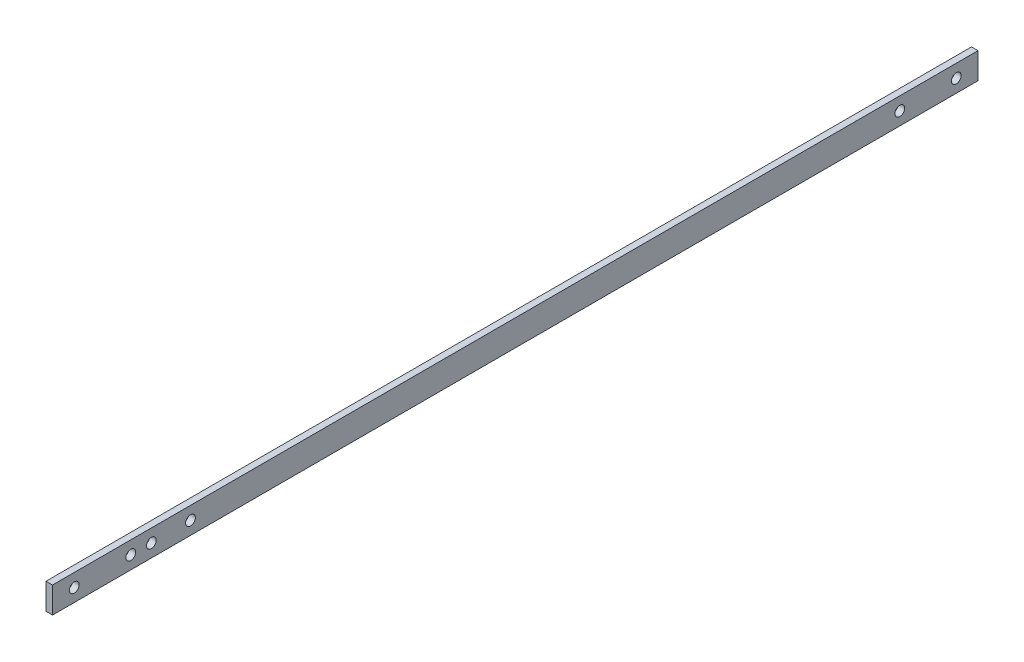
SolidWorks part; units mm, degrees
ref_plane "前视基准面" through (0, 0, 0) normal (0, 0, 1) x (1, 0, 0)
ref_plane "上视基准面" through (0, 0, 0) normal (0, 1, 0) x (1, 0, 0)
ref_plane "右视基准面" through (0, 0, 0) normal (1, 0, 0) x (0, 0, -1)
other "Configuration Table"
sketch "草图1" plane through (0, 0, 0) normal (1, 0, 0) x (0, 0, -1)
  line L1 (0, 0) -> (426, 0)
  line L2 (0, 0) -> (0, 12)
  line L3 (0, 12) -> (426, 12)
  line L4 (426, 0) -> (426, 12)
  circle A0 centre (10, 6) radius 2.25
  circle A1 centre (416, 6) radius 2.25
  circle A2 centre (36, 6) radius 2.25
  circle A3 centre (390, 6) radius 2.25
  circle A4 centre (45.5, 6) radius 2.25
  circle A5 centre (63.5, 6) radius 2.25
  dimension "D3" = 6
  dimension "D5" = 4.5
  dimension "D6" = 6
  dimension "D7" = 10
  dimension "D8" = 26
  dimension "D9" = 26
  dimension "D10" = 6
  dimension "D11" = 9.5
  dimension "D12" = 18
  dimension "D13" = 6
  dimension "D14" = 6
  dimension "D15" = 6
  dimension "D1" = 426
  dimension "D2" = 12
  dimension "D4" = 10
extrude "凸台-拉伸1" add sketch "草图1" along normal blind 3
